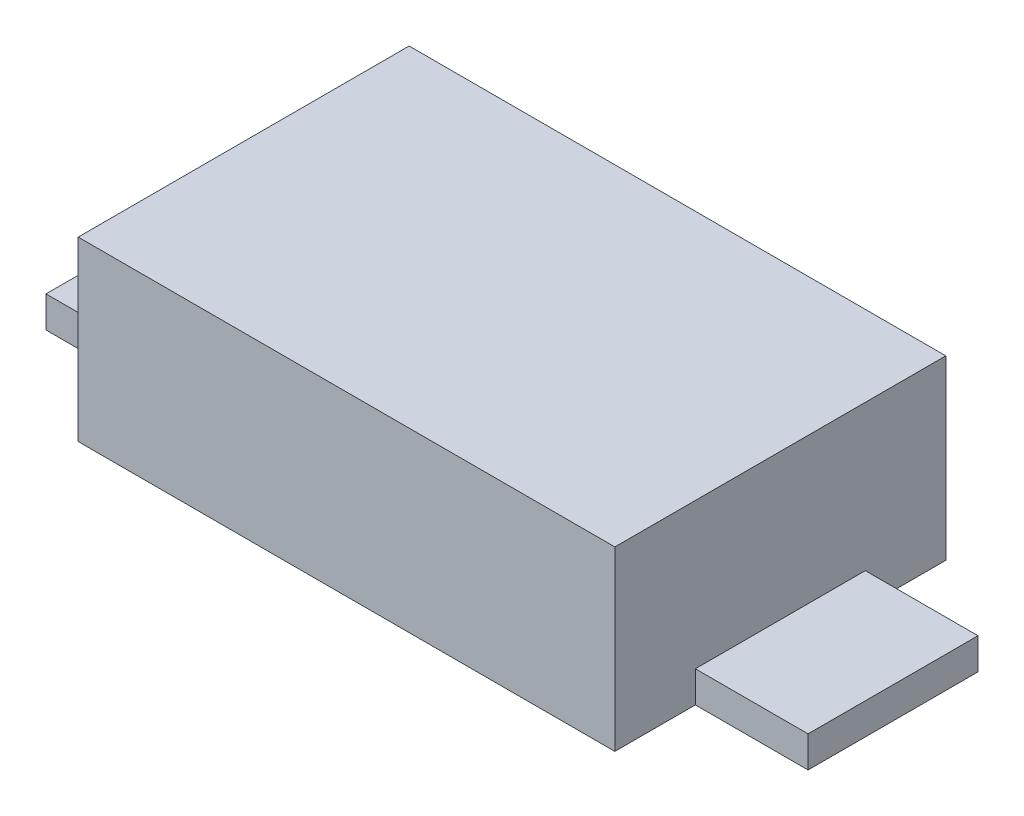
SolidWorks part; units mm, degrees
ref_plane "Front Plane" through (0, 0, 0) normal (0, 0, 1) x (1, 0, 0)
ref_plane "Top Plane" through (0, 0, 0) normal (0, 1, 0) x (1, 0, 0)
ref_plane "Right Plane" through (0, 0, 0) normal (1, 0, 0) x (0, 0, -1)
sketch "Sketch2" plane through (0, 0, 0) normal (0, 1, 0) x (1, 0, 0)
  line L1 (-4.5326, -4.1326) -> (-1.5326, -4.1326)
  line L2 (-4.5326, -4.1326) -> (-4.5326, -2.2826)
  line L3 (-4.5326, -2.2826) -> (-1.5326, -2.2826)
  line L4 (-1.5326, -4.1326) -> (-1.5326, -2.2826)
  dimension "D1" = 3
  dimension "D2" = 1.85
extrude "Boss-Extrude1" add sketch "Sketch2" along normal blind 0.99
sketch "Sketch3" plane through (0, 0, 0) normal (0, 1, 0) x (1, 0, 0)
  line L0 (-4.5326, -2.2826) -> (-4.5326, -4.1326) construction
  line L1 (-4.5326, -2.7326) -> (-5.1626, -2.7326)
  line L2 (-4.5326, -2.7326) -> (-4.5326, -3.6826)
  line L3 (-4.5326, -3.6826) -> (-5.1626, -3.6826)
  line L4 (-5.1626, -2.7326) -> (-5.1626, -3.6826)
  line L5 (-1.5326, -4.1326) -> (-1.5326, -2.2826) construction
  line L6 (-1.5326, -2.7326) -> (-0.9026, -2.7326)
  line L7 (-1.5326, -2.7326) -> (-1.5326, -3.6826)
  line L8 (-1.5326, -3.6826) -> (-0.9026, -3.6826)
  line L9 (-0.9026, -2.7326) -> (-0.9026, -3.6826)
  point P14 (-4.5326, -3.2076)
  dimension "D1" = 0.63
  dimension "D2" = 0.63
  dimension "D3" = 0.95
  dimension "D4" = 0.95
  dimension "D5" = 0.45
  dimension "D6" = 0.45
  dimension "D7" = 0.45
  dimension "D8" = 0.45
extrude "Boss-Extrude2" add sketch "Sketch3" along normal blind 0.175
